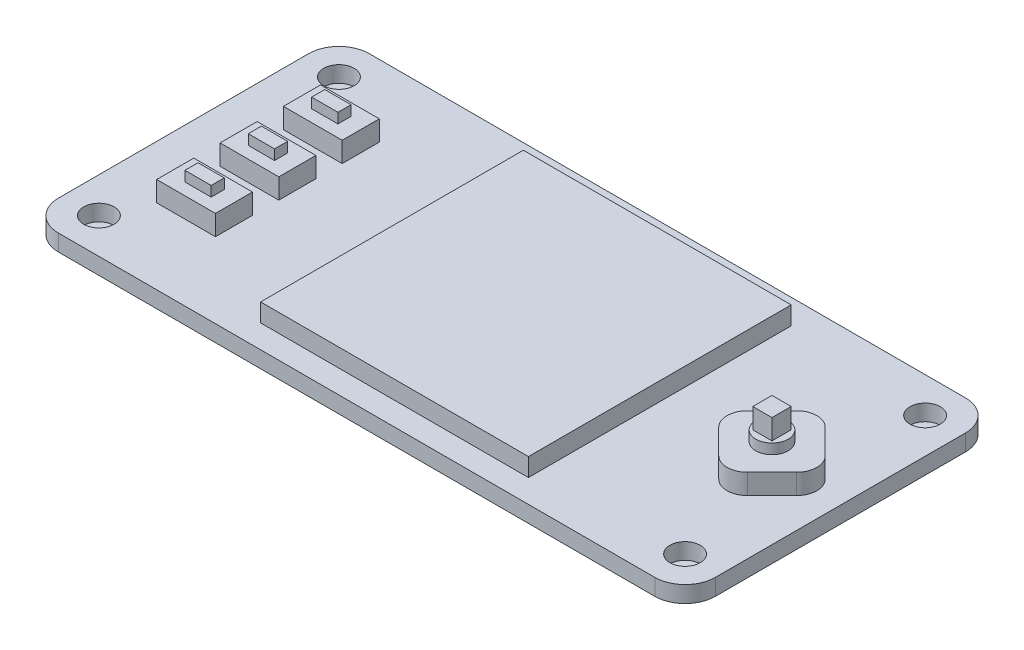
SolidWorks part; units mm, degrees
ref_plane "前视基准面" through (0, 0, 0) normal (0, 0, 1) x (1, 0, 0)
ref_plane "上视基准面" through (0, 0, 0) normal (0, 1, 0) x (1, 0, 0)
ref_plane "右视基准面" through (0, 0, 0) normal (1, 0, 0) x (0, 0, -1)
sketch "草图1" plane through (0, 0, 0) normal (0, 1, 0) x (1, 0, 0)
  line L1 (-29.5, 15.375) -> (29.5, 15.375)
  line L2 (-32.5, 12.375) -> (-32.5, -12.375)
  line L3 (-29.5, -15.375) -> (29.5, -15.375)
  line L4 (32.5, 12.375) -> (32.5, -12.375)
  line L5 (-32.5, 15.375) -> (32.5, -15.375) construction
  line L6 (-32.5, -15.375) -> (32.5, 15.375) construction
  arc A0 (-32.5, -12.375) -> (-29.5, -15.375) centre (-29.5, -12.375) ccw
  arc A1 (29.5, -15.375) -> (32.5, -12.375) centre (29.5, -12.375) ccw
  arc A2 (29.5, 15.375) -> (32.5, 12.375) centre (29.5, 12.375) cw
  arc A3 (-29.5, 15.375) -> (-32.5, 12.375) centre (-29.5, 12.375) ccw
  point P0 (0, 0)
  dimension "D3" = 3
  dimension "D1" = 30.75
  dimension "D2" = 65
extrude "凸台-拉伸1" add sketch "草图1" along normal blind 1.63
sketch "草图2" plane through (0, 1.63, 0) normal (0, 1, 0) x (1, 0, 0)
  line L0 (29.5, 15.375) -> (-29.5, 15.375) construction
  line L2 (-32.5, 12.375) -> (-32.5, -12.375) construction
  line L3 (-29.5, -15.375) -> (29.5, -15.375) construction
  line L4 (32.5, -12.375) -> (32.5, 12.375) construction
  circle A0 centre (-29, 11.875) radius 1.5
  circle A1 centre (-29, -11.875) radius 1.5
  circle A2 centre (29, -11.875) radius 1.5
  circle A3 centre (29, 11.875) radius 1.5
  dimension "D1" = 3
  dimension "D2" = 3.5
  dimension "D3" = 3.5
  dimension "D4" = 3.5
  dimension "D5" = 3.5
extrude "切除-拉伸1" cut sketch "草图2" against normal blind 1.6
sketch "草图3" plane through (0, 1.63, 0) normal (0, 1, 0) x (1, 0, 0)
  line L0 (-29.5, -15.375) -> (29.5, -15.375) construction
  line L1 (-11.8, 12.925) -> (14.7, 12.925)
  line L2 (-11.8, 12.925) -> (-11.8, -13.075)
  line L3 (-11.8, -13.075) -> (14.7, -13.075)
  line L4 (14.7, 12.925) -> (14.7, -13.075)
  line L7 (32.5, -12.375) -> (32.5, 12.375) construction
  dimension "D1" = 26
  dimension "D2" = 26.5
  dimension "D3" = 2.3
  dimension "D4" = 17.8
sketch "草图4" plane through (0, 1.63, 0) normal (0, 1, 0) x (1, 0, 0)
  line L0 (-29.5, -15.375) -> (29.5, -15.375) construction
  line L1 (-27.23, 8.285) -> (-21.42, 8.285)
  line L2 (-27.23, 8.285) -> (-27.23, 4.615)
  line L3 (-27.23, 4.615) -> (-21.42, 4.615)
  line L4 (-21.42, 8.285) -> (-21.42, 4.615)
  line L5 (-27.23, 2.015) -> (-21.42, 2.015)
  line L6 (-27.23, 2.015) -> (-27.23, -1.655)
  line L7 (-27.23, -1.655) -> (-21.42, -1.655)
  line L8 (-21.42, 2.015) -> (-21.42, -1.655)
  line L9 (-27.23, -4.255) -> (-21.42, -4.255)
  line L10 (-27.23, -4.255) -> (-27.23, -7.925)
  line L11 (-27.23, -7.925) -> (-21.42, -7.925)
  line L12 (-21.42, -4.255) -> (-21.42, -7.925)
  line L13 (-32.5, 12.375) -> (-32.5, -12.375) construction
  dimension "D1" = 5.81
  dimension "D2" = 3.67
  dimension "D3" = 2.6
  dimension "D4" = 2.6
  dimension "D5" = 7.45
  dimension "D6" = 5.27
sketch "草图5" plane through (0, 1.63, 0) normal (0, 1, 0) x (1, 0, 0)
  line L0 (27.0747, 3.9183) -> (29.5142, 1.4787)
  line L1 (24.2463, 3.9183) -> (21.8067, 1.4787)
  line L2 (29.5142, -1.3497) -> (27.0747, -3.7892)
  line L3 (21.8067, -1.3497) -> (24.2463, -3.7892)
  line L4 (32.5, -12.375) -> (32.5, 12.375) construction
  line L5 (-29.5, -15.375) -> (29.5, -15.375) construction
  arc A0 (27.0747, -3.7892) -> (24.2463, -3.7892) centre (25.6605, -2.375) cw
  arc A1 (21.8067, 1.4787) -> (21.8067, -1.3497) centre (23.221, 0.0645) ccw
  arc A2 (24.2463, 3.9183) -> (27.0747, 3.9183) centre (25.6605, 2.504) cw
  arc A3 (29.5142, 1.4787) -> (29.5142, -1.3497) centre (28.1, 0.0645) cw
  point P8 (20.3925, 0.0645)
  point P11 (25.6605, 5.3325)
  point P14 (30.9284, 0.0645)
  point P15 (30.1, 0.0645)
  point P18 (25.6605, -4.375)
  dimension "D3" = 2
  dimension "D1" = 7.45
  dimension "D2" = 7.45
  dimension "D4" = 2.4
  dimension "D5" = 11
extrude "凸台-拉伸2" add sketch "草图3" along normal blind 1.8
extrude "凸台-拉伸3" add sketch "草图5" along normal blind 2
extrude "凸台-拉伸4" add sketch "草图4" along normal blind 2
sketch "草图7" plane through (0, 3.63, 0) normal (0, 1, 0) x (1, 0, 0)
  line L0 (-21.42, 8.285) -> (-27.23, 8.285) construction
  line L1 (-25.625, 7.1) -> (-23.025, 7.1)
  line L2 (-25.625, 7.1) -> (-25.625, 5.8)
  line L3 (-25.625, 5.8) -> (-23.025, 5.8)
  line L4 (-23.025, 7.1) -> (-23.025, 5.8)
  line L5 (-25.625, 7.1) -> (-23.025, 5.8) construction
  line L6 (-25.625, 5.8) -> (-23.025, 7.1) construction
  line L7 (-25.625, 0.83) -> (-23.025, 0.83)
  line L8 (-25.625, 0.83) -> (-25.625, -0.47)
  line L9 (-25.625, -0.47) -> (-23.025, -0.47)
  line L10 (-23.025, 0.83) -> (-23.025, -0.47)
  line L11 (-25.625, 0.83) -> (-23.025, -0.47) construction
  line L12 (-25.625, -0.47) -> (-23.025, 0.83) construction
  line L13 (-25.625, -5.44) -> (-23.025, -5.44)
  line L14 (-25.625, -5.44) -> (-25.625, -6.74)
  line L15 (-25.625, -6.74) -> (-23.025, -6.74)
  line L16 (-23.025, -5.44) -> (-23.025, -6.74)
  line L17 (-25.625, -5.44) -> (-23.025, -6.74) construction
  line L18 (-25.625, -6.74) -> (-23.025, -5.44) construction
  line L19 (-27.23, -4.255) -> (-27.23, -7.925) construction
  line L20 (-27.23, 2.015) -> (-27.23, -1.655) construction
  line L21 (-27.23, 8.285) -> (-27.23, 4.615) construction
  point P0 (-24.325, 6.45)
  point P5 (-24.325, 0.18)
  point P10 (-24.325, -6.09)
  point P18 (-24.325, 8.285)
  point P22 (-27.23, -6.09)
  point P26 (-27.23, 0.18)
  point P30 (-27.23, 6.45)
  dimension "D1" = 2.6
  dimension "D2" = 1.3
extrude "凸台-拉伸5" add sketch "草图7" along normal blind 1
sketch "草图8" plane through (0, 0, 0) normal (0, -1, 0) x (1, 0, 0)
  line L0 (29.5, -15.375) -> (-29.5, -15.375) construction
  line L1 (-25.7, -8.735) -> (25.3, -8.735)
  line L2 (-25.7, -8.735) -> (-25.7, -13.735)
  line L3 (-25.7, -13.735) -> (25.3, -13.735)
  line L4 (25.3, -8.735) -> (25.3, -13.735)
  line L5 (32.5, 12.375) -> (32.5, -12.375) construction
  dimension "D1" = 5
  dimension "D2" = 51
  dimension "D3" = 1.64
  dimension "D4" = 7.2
extrude "凸台-拉伸6" add sketch "草图8" along normal blind 3.68
sketch "草图9" plane through (0, 3.63, 0) normal (0, 1, 0) x (1, 0, 0)
  line L1 (24.7105, 1.0145) -> (26.6105, 1.0145)
  line L2 (24.7105, 1.0145) -> (24.7105, -0.8855)
  line L3 (24.7105, -0.8855) -> (26.6105, -0.8855)
  line L4 (26.6105, 1.0145) -> (26.6105, -0.8855)
  line L5 (24.7105, 1.0145) -> (26.6105, -0.8855) construction
  line L6 (24.7105, -0.8855) -> (26.6105, 1.0145) construction
  arc A0 (29.5142, -1.3497) -> (29.5142, 1.4787) centre (28.1, 0.0645) ccw construction
  arc A1 (27.0747, 3.9183) -> (24.2463, 3.9183) centre (25.6605, 2.504) ccw construction
  point P0 (25.6605, 0.0645)
  point P11 (30.1, 0.0645)
  point P16 (25.6605, 4.504)
  dimension "D1" = 1.9
extrude "凸台-拉伸7" add sketch "草图9" along normal blind 3
sketch "草图10" plane through (0, 3.63, 0) normal (0, 1, 0) x (1, 0, 0)
  line L0 (26.6105, 1.0145) -> (24.7105, 1.0145) construction
  line L2 (26.6105, -0.8855) -> (26.6105, 1.0145) construction
  circle A0 centre (25.6605, 0.0645) radius 1.6
  point P5 (25.6605, 1.0145)
  point P11 (26.6105, 0.0645)
  dimension "D1" = 3.2
extrude "凸台-拉伸8" add sketch "草图10" along normal blind 1
